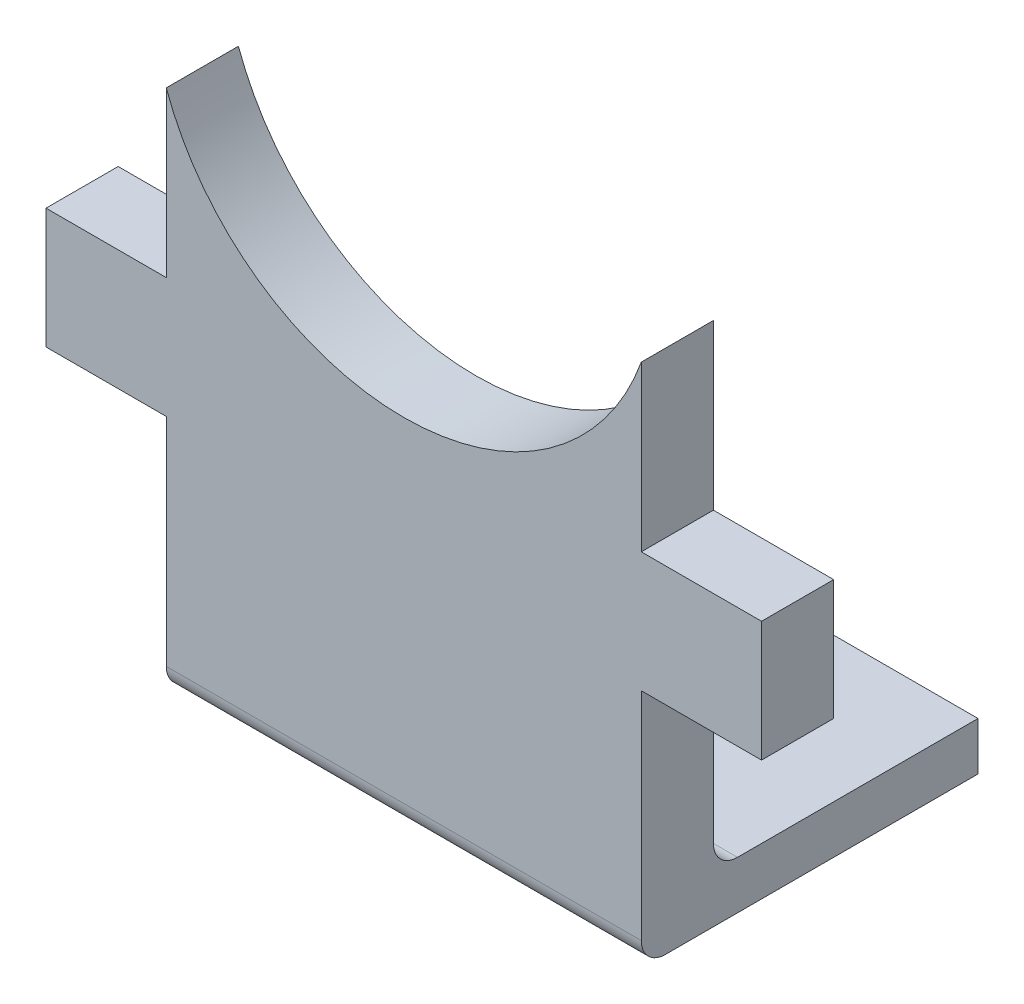
SolidWorks part; units mm, degrees
material "PLA"
ref_plane "Alzado" through (0, 0, 0) normal (0, 0, 1) x (1, 0, 0)
ref_plane "Planta" through (0, 0, 0) normal (0, 1, 0) x (1, 0, 0)
ref_plane "Vista lateral" through (0, 0, 0) normal (1, 0, 0) x (0, 0, -1)
sketch "Croquis1" plane through (0, 0, 0) normal (0, 0, 1) x (1, 0, 0)
  line L0 (-9.875, 0) -> (-9.875, -25.4)
  line L1 (-9.875, -25.4) -> (9.875, -25.4)
  line L2 (9.875, -25.4) -> (9.875, 0)
  line L4 (-9.875, -10.4) -> (-14.875, -10.4)
  line L5 (-9.875, -10.4) -> (-9.875, -15.4)
  line L6 (-9.875, -15.4) -> (-14.875, -15.4)
  line L7 (-14.875, -10.4) -> (-14.875, -15.4)
  line L8 (9.875, -10.4) -> (14.875, -10.4)
  line L9 (9.875, -10.4) -> (9.875, -15.4)
  line L10 (9.875, -15.4) -> (14.875, -15.4)
  line L11 (14.875, -10.4) -> (14.875, -15.4)
  circle A0 centre (0, 0) radius 9.875
  dimension "D1" = 19.75
  dimension "D2" = 25.4
  dimension "D3" = 5
  dimension "D4" = 5
  dimension "D5" = 5
  dimension "D6" = 5
  dimension "D7" = 10
  dimension "D8" = 10
extrude "Saliente-Extruir1" add sketch "Croquis1" along normal blind 3 contours A0 | A0 L0 L1 L2 | L11 L8 L2 L10 | L4 L7 L6 L0
fillet "Redondeo1" radius 1 1 edges at (0, -25.4, 3)
sketch "Croquis2" plane through (0, 0, 3) normal (0, 0, 1) x (1, 0, 0)
  circle A0 centre (0, 0) radius 10.5
  dimension "D1" = 21
extrude "Cortar-Extruir1" cut sketch "Croquis2" against normal blind 10
sketch "Croquis3" plane through (0, 0, 0) normal (0, 0, -1) x (-1, 0, 0)
  line L0 (9.875, -15.4) -> (9.875, -25.4) construction
  line L1 (-9.875, -25.4) -> (9.875, -25.4)
  line L2 (-9.875, -25.4) -> (-9.875, -23.4)
  line L3 (-9.875, -23.4) -> (9.875, -23.4)
  line L4 (9.875, -25.4) -> (9.875, -23.4)
  dimension "D1" = 2
extrude "Saliente-Extruir2" add sketch "Croquis3" along normal blind 11
fillet "Redondeo2" radius 1 1 edges at (0, -23.4, 0)
